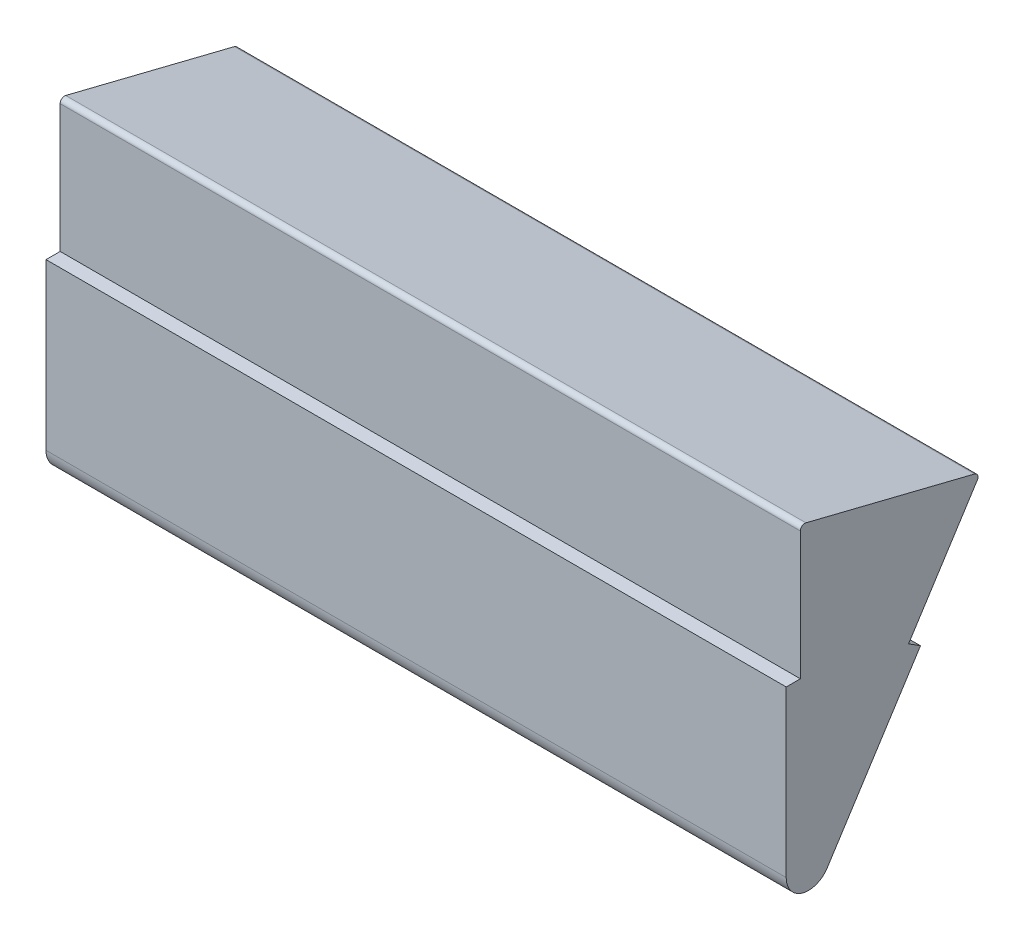
SolidWorks part; units mm, degrees
material "ABS"
ref_plane "Front Plane" through (0, 0, 0) normal (0, 0, 1) x (1, 0, 0)
ref_plane "Top Plane" through (0, 0, 0) normal (0, 1, 0) x (1, 0, 0)
ref_plane "Right Plane" through (0, 0, 0) normal (1, 0, 0) x (0, 0, -1)
sketch "Sketch1" plane through (0, 0, 0) normal (1, 0, 0) x (0, 0, -1)
  line L0 (0, 17.0881) -> (0, 35) construction
  line L3 (0, 35) -> (3.175, 35) construction
  line L6 (3.175, 35) -> (3.175, 65) construction
  line L11 (0, 17.0881) -> (0, 0) construction
  line L17 (43.6351, 54.921) -> (27.5822, 29.8381) construction
  line L19 (27.5822, 29.8381) -> (27.4636, 29.6528) construction
  line L23 (27.4636, 29.6528) -> (30.1378, 27.9413) construction
  line L25 (30.1378, 27.9413) -> (8.6944, -5.5644) construction
  line L26 (0, 35) -> (0, -19.1494) construction
  line L28 (3.175, 65) -> (43.6351, 54.921) construction
  line L29 (8.6944, -5.5644) -> (0, -19.1494) construction
  line L30 (0, 35) -> (3.175, 35)
  line L31 (3.175, 35) -> (3.175, 63.7203)
  line L32 (4.4167, 64.6907) -> (42.2839, 55.2576)
  line L33 (42.8845, 53.7482) -> (27.4636, 29.6528)
  line L34 (27.4636, 29.6528) -> (30.1378, 27.9413)
  line L35 (30.1378, 27.9413) -> (9.2114, -4.7565)
  line L36 (0, -2.0613) -> (0, 35)
  arc A0 (9.2114, -4.7565) -> (0, -2.0613) centre (5, -2.0613) cw
  arc A1 (42.2839, 55.2576) -> (42.8845, 53.7482) centre (42.0422, 54.2872) cw
  arc A2 (3.175, 63.7203) -> (4.4167, 64.6907) centre (4.175, 63.7203) cw
  point P6 (0, 0)
  dimension "D2" = 30
  dimension "D3" = 3.175
  dimension "D8" = 3.175
  dimension "D5" = 5
  dimension "D9" = 1
  dimension "D1" = 32.619
  dimension "D4" = 35
  dimension "D6" = 30
  dimension "D7" = 41.6966
  dimension "D10" = 54.1494
extrude "Boss-Extrude1" add sketch "Sketch1" along normal blind 166.124
